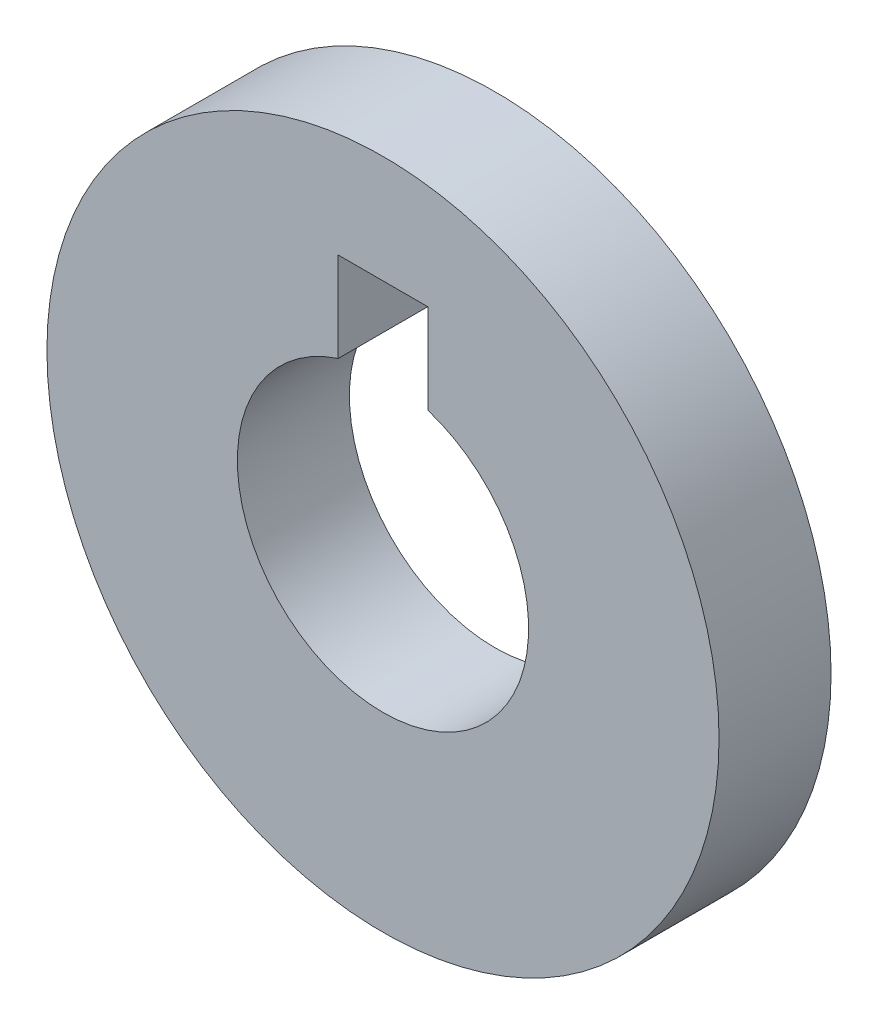
SolidWorks part; units mm, degrees
ref_plane "Ön Düzlem" through (0, 0, 0) normal (0, 0, 1) x (1, 0, 0)
ref_plane "Üst Düzlem" through (0, 0, 0) normal (0, 1, 0) x (1, 0, 0)
ref_plane "Sağ Düzlem" through (0, 0, 0) normal (1, 0, 0) x (0, 0, -1)
sketch "Çizim1" plane through (0, 0, 0) normal (0, 0, 1) x (1, 0, 0)
  circle A0 centre (0, 0) radius 15
  circle A1 centre (0, 0) radius 6.5
  dimension "D1" = 30
  dimension "D2" = 13
extrude "Yükseklik-Ekstrüzyon1" add sketch "Çizim1" along normal blind 5
sketch "Çizim2" plane through (0, 0, 0) normal (0, 0, -1) x (-1, 0, 0)
  line L1 (-2, 10.1847) -> (2, 10.1847)
  line L2 (-2, 10.1847) -> (-2, 6.1847)
  line L3 (-2, 6.1847) -> (2, 6.1847)
  line L4 (2, 10.1847) -> (2, 6.1847)
  circle A0 centre (0, 0) radius 6.5 construction
  dimension "D1" = 2
  dimension "D2" = 2
  dimension "D3" = 4
extrude "Kes-Ekstrüzyon1" cut sketch "Çizim2" against normal blind 8
